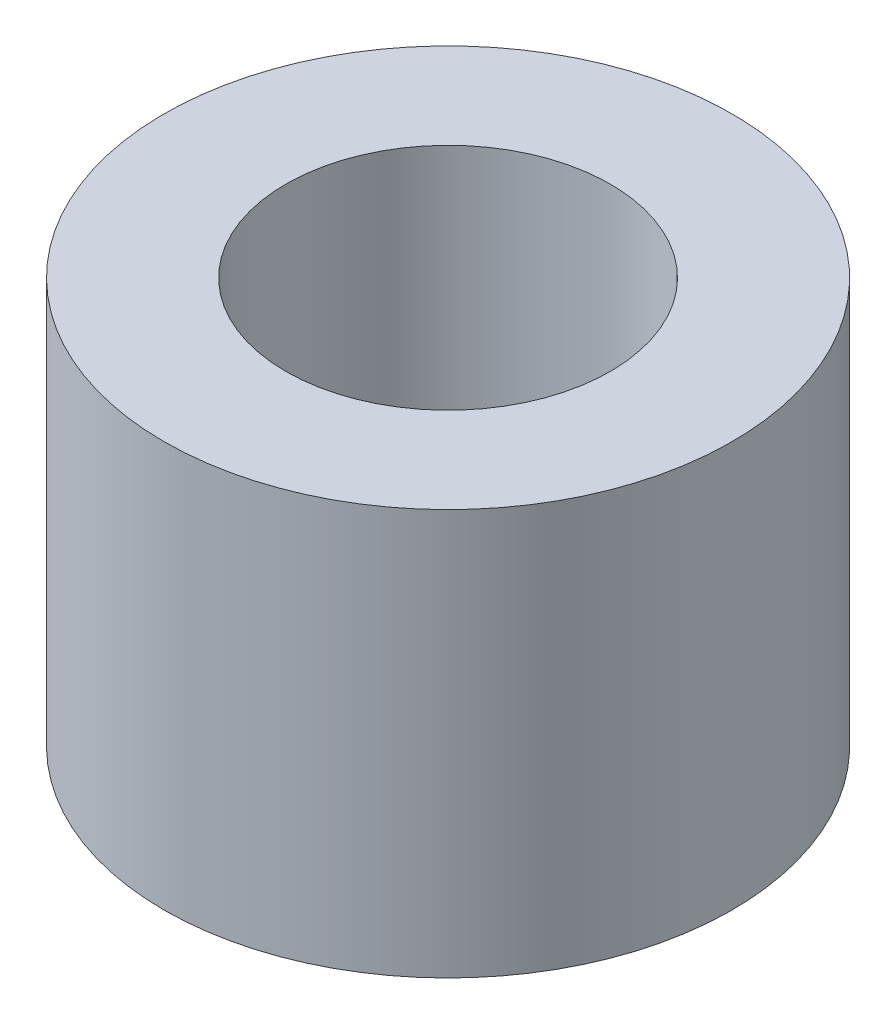
SolidWorks part; units mm, degrees
ref_plane "Płaszczyzna przednia" through (0, 0, 0) normal (0, 0, 1) x (1, 0, 0)
ref_plane "Płaszczyzna górna" through (0, 0, 0) normal (0, 1, 0) x (1, 0, 0)
ref_plane "Płaszczyzna prawa" through (0, 0, 0) normal (1, 0, 0) x (0, 0, -1)
sketch "Szkic1" plane through (0, 0, 0) normal (0, 1, 0) x (1, 0, 0)
  circle A0 centre (0, 0) radius 2
  circle A1 centre (0, 0) radius 3.5
  dimension "D1" = 4
  dimension "D2" = 7
extrude "Dodanie-wyciągnięcie1" add sketch "Szkic1" along normal blind 5
